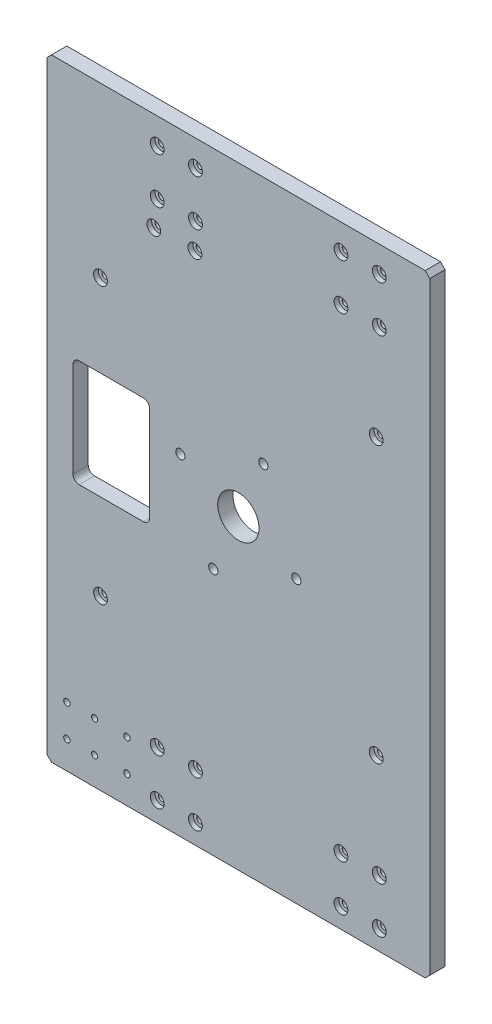
SolidWorks part; units mm, degrees
ref_plane "Plan de face" through (0, 0, 0) normal (0, 0, 1) x (1, 0, 0)
ref_plane "Plan de dessus" through (0, 0, 0) normal (0, 1, 0) x (1, 0, 0)
ref_plane "Plan de droite" through (0, 0, 0) normal (1, 0, 0) x (0, 0, -1)
sketch "Esquisse1" plane through (0, 0, 0) normal (0, 0, 1) x (1, 0, 0)
  line L1 (-125, -200) -> (125, -200)
  line L2 (-125, -200) -> (-125, 200)
  line L3 (-125, 200) -> (125, 200)
  line L4 (125, -200) -> (125, 200)
  line L5 (-125, -200) -> (125, 200) construction
  line L6 (-125, 200) -> (125, -200) construction
  point P0 (0, 0)
  dimension "D1" = 400
  dimension "D2" = 250
extrude "Boss.-Extru.1" add sketch "Esquisse1" along normal blind 10
ref_plane "Plan1" through (0, 0, 0) normal (1, 0, 0) x (0, 0, -1)
ref_plane "Plan2" through (0, 0, 0) normal (0, 1, 0) x (1, 0, 0)
sketch "Esquisse2" plane through (0, 0, 0) normal (0, 0, -1) x (-1, 0, 0)
  circle A0 centre (0, 0) radius 13.5
  dimension "D1" = 27
extrude "Enlèv. mat.-Extru.1" cut sketch "Esquisse2" against normal through all
chamfer "Chanfrein1" distance 3 angle 45 4 edges at (-125, -200, 5) (125, -200, 5) (125, 200, 5) (-125, 200, 5)
hole_wizard "Trou taraudé M51" positions "Esquisse6" profile "Esquisse5" tap size "M5" standard "ISO" end condition through all
sketch "Esquisse6" plane through (0, 0, 10) normal (0, 0, 1) x (1, 0, 0)
  point P0 (-72.6985, -161.0797)
  point P3 (-72.6985, -181.8387)
  point P6 (-111.9372, -181.8387)
  point P9 (-111.9372, -161.0797)
sketch "Esquisse5" plane through (-72.6985, -161.0797, 10) normal (1, 0, 0) x (0, -1, 0)
  line L0 (0, 0) -> (0, 10)
  line L1 (0, 10) -> (2.1, 10)
  line L2 (2.1, 10) -> (2.1, 0)
  line L5 (2.1, 0) -> (0, 0)
  line L11 (0, -6.35) -> (0, 107.95) construction
  dimension "Diamètre du trou pour taraudage jusqu'au prochain" = 4.2
  dimension "Profondeur du trou pour taraudage jusqu'au prochain" = 10
cosmetic thread "Filetage de perçage3" parameters "D2"=5
cosmetic thread "Filetage de perçage4" parameters "D2"=5
cosmetic thread "Filetage de perçage5" parameters "D2"=5
cosmetic thread "Filetage de perçage6" parameters "D2"=5
hole_wizard "Trous de centrage Ø4.0mm2" positions "Esquisse9" profile "Esquisse8" hole size "Ø4.0" standard "ISO" end condition through all
sketch "Esquisse9" plane through (0, 0, 10) normal (0, 0, 1) x (1, 0, 0)
  point P0 (-93.8631, -161.0797)
  point P3 (-93.8631, -181.8387)
sketch "Esquisse8" plane through (-93.8631, -161.0797, 10) normal (1, 0, 0) x (0, -1, 0)
  line L0 (0, 0) -> (0, 10)
  line L1 (0, 10) -> (2, 10)
  line L2 (2, 10) -> (2, 0)
  line L5 (2, 0) -> (0, 0)
  line L11 (0, -6.35) -> (0, 107.95) construction
  dimension "Diamètre du perçage jusqu'au prochain" = 4
  dimension "Profondeur du perçage jusqu'au prochain" = 10
sketch "Esquisse10" plane through (0, 0, 10) normal (0, 0, 1) x (1, 0, 0)
  circle A0 centre (0, 0) radius 41.25 construction
  dimension "D1" = 82.5
hole_wizard "Trous de centrage Ø6.0mm2" positions "Esquisse26" profile "Esquisse25" hole size "Ø6.0" standard "ISO" end condition through all
sketch "Esquisse26" plane through (0, 0, 10) normal (0, 0, 1) x (1, 0, 0)
  point P0 (16.3571, 37.8683)
  point P2 (37.8683, -16.3571)
  point P4 (-16.3571, -37.8683)
  point P6 (-37.8683, 16.3571)
sketch "Esquisse25" plane through (16.3571, 37.8683, 10) normal (1, 0, 0) x (0, -1, 0)
  line L0 (0, 0) -> (0, 10)
  line L1 (0, 10) -> (3, 10)
  line L2 (3, 10) -> (3, 0)
  line L5 (3, 0) -> (0, 0)
  line L11 (0, -6.35) -> (0, 107.95) construction
  dimension "Diamètre du perçage jusqu'au prochain" = 6
  dimension "Profondeur du perçage jusqu'au prochain" = 10
hole_wizard "Dégagement M41" positions "Esquisse28" profile "Esquisse27" hole size "M4" standard "JIS" end condition through all
sketch "Esquisse28" plane through (0, 0, 0) normal (0, 0, -1) x (-1, 0, 0)
  point P0 (28, -187)
  point P2 (28, -157)
  point P4 (53, -157)
  point P6 (53, -187)
sketch "Esquisse27" plane through (-28, -187, 0) normal (1, 0, 0) x (0, 1, 0)
  line L0 (0, 0) -> (0, 10)
  line L1 (0, 10) -> (2.25, 10)
  line L2 (2.25, 10) -> (2.25, 0)
  line L5 (2.25, 0) -> (0, 0)
  line L11 (0, -6.35) -> (0, 107.95) construction
  dimension "Diamètre du perçage jusqu'au prochain" = 4.5
  dimension "Profondeur du perçage jusqu'au prochain" = 10
pattern_linear "Répétition linéaire1" count 2 spacing 120 along (1, 0, 0) count 2 spacing 340 along (0, 1, 0) of "Dégagement M41"
hole_wizard "Chambrage pour vis à tête ronde bombée M41" positions "Esquisse30" profile "Esquisse29" counterbore size "M4" standard "Ansi Metric" end condition through all
sketch "Esquisse30" plane through (0, 0, 10) normal (0, 0, 1) x (1, 0, 0)
  point P0 (92, -157)
sketch "Esquisse29" plane through (92, -157, 10) normal (1, 0, 0) x (0, -1, 0)
  line L0 (0, 0) -> (0, 10)
  line L1 (0, 10) -> (2.25, 10)
  line L2 (2.25, 3.125) -> (2.25, 10)
  line L3 (2.25, 3.125) -> (2.275, 3.1)
  line L4 (2.275, 3.1) -> (4.5, 3.1)
  line L5 (4.5, 3.1) -> (4.5, 0)
  line L7 (0, 0) -> (4.5, 0)
  line L9 (-2.25, 3.125) -> (-2.275, 3.1) construction
  line L11 (0, -6.35) -> (0, 107.95) construction
  dimension "Diamètre du perçage jusqu'au prochain" = 4.5
  dimension "Profondeur du perçage jusqu'au prochain" = 10
  dimension "Diamètre du chambrage" = 9
  dimension "Profondeur du chambrage" = 3.1
  dimension "Diamètre du fraisage milieu" = 4.55
  dimension "Angle du fraisage milieu" = 90
pattern_linear "Répétition linéaire2" count 2 spacing 30 along (0, -1, 0) count 2 spacing 25 along (-1, 0, 0) of "Chambrage pour vis à tête ronde bombée M41"
pattern_linear "Répétition linéaire3" count 2 spacing 120 along (-1, 0, 0) count 2 spacing 340 along (0, 1, 0) of "Répétition linéaire2", "Chambrage pour vis à tête ronde bombée M41"
hole_wizard "Dégagement M42" positions "Esquisse32" profile "Esquisse31" hole size "M4" standard "JIS" end condition through all
sketch "Esquisse32" plane through (0, 0, 0) normal (0, 0, -1) x (-1, 0, 0)
  point P0 (90, -90)
  point P2 (90, 90)
  point P4 (-90, 90)
  point P6 (-90, -90)
sketch "Esquisse31" plane through (-90, -90, 0) normal (1, 0, 0) x (0, 1, 0)
  line L0 (0, 0) -> (0, 10)
  line L1 (0, 10) -> (2.25, 10)
  line L2 (2.25, 10) -> (2.25, 0)
  line L5 (2.25, 0) -> (0, 0)
  line L11 (0, -6.35) -> (0, 107.95) construction
  dimension "Diamètre du perçage jusqu'au prochain" = 4.5
  dimension "Profondeur du perçage jusqu'au prochain" = 10
hole_wizard "Chambrage pour vis à tête ronde bombée M42" positions "Esquisse34" profile "Esquisse33" counterbore size "M4" standard "Ansi Metric" end condition through all
sketch "Esquisse34" plane through (0, 0, 10) normal (0, 0, 1) x (1, 0, 0)
  point P0 (-90, -90)
  point P2 (-90, 90)
  point P4 (90, -90)
  point P6 (90, 90)
sketch "Esquisse33" plane through (-90, -90, 10) normal (1, 0, 0) x (0, -1, 0)
  line L0 (0, 0) -> (0, 10)
  line L1 (0, 10) -> (2.25, 10)
  line L2 (2.25, 3.125) -> (2.25, 10)
  line L3 (2.25, 3.125) -> (2.275, 3.1)
  line L4 (2.275, 3.1) -> (4.5, 3.1)
  line L5 (4.5, 3.1) -> (4.5, 0)
  line L7 (0, 0) -> (4.5, 0)
  line L9 (-2.25, 3.125) -> (-2.275, 3.1) construction
  line L11 (0, -6.35) -> (0, 107.95) construction
  dimension "Diamètre du perçage jusqu'au prochain" = 4.5
  dimension "Profondeur du perçage jusqu'au prochain" = 10
  dimension "Diamètre du chambrage" = 9
  dimension "Profondeur du chambrage" = 3.1
  dimension "Diamètre du fraisage milieu" = 4.55
  dimension "Angle du fraisage milieu" = 90
hole_wizard "Dégagement M43" positions "Esquisse36" profile "Esquisse35" hole size "M4" standard "JIS" end condition through all
sketch "Esquisse36" plane through (0, 0, 0) normal (0, 0, -1) x (-1, 0, 0)
  point P0 (55.199, 135.7065)
  point P2 (28.3418, 135.9918)
sketch "Esquisse35" plane through (-55.199, 135.7065, 0) normal (1, 0, 0) x (0, 1, 0)
  line L0 (0, 0) -> (0, 10)
  line L1 (0, 10) -> (2.25, 10)
  line L2 (2.25, 10) -> (2.25, 0)
  line L5 (2.25, 0) -> (0, 0)
  line L11 (0, -6.35) -> (0, 107.95) construction
  dimension "Diamètre du perçage jusqu'au prochain" = 4.5
  dimension "Profondeur du perçage jusqu'au prochain" = 10
hole_wizard "Chambrage pour vis à tête ronde bombée M43" positions "Esquisse38" profile "Esquisse37" counterbore size "M4" standard "Ansi Metric" end condition through all
sketch "Esquisse38" plane through (0, 0, 10) normal (0, 0, 1) x (1, 0, 0)
  point P0 (-55.199, 135.7065)
  point P2 (-28.3418, 135.9918)
sketch "Esquisse37" plane through (-55.199, 135.7065, 10) normal (1, 0, 0) x (0, -1, 0)
  line L0 (0, 0) -> (0, 10)
  line L1 (0, 10) -> (2.25, 10)
  line L2 (2.25, 3.125) -> (2.25, 10)
  line L3 (2.25, 3.125) -> (2.275, 3.1)
  line L4 (2.275, 3.1) -> (4.5, 3.1)
  line L5 (4.5, 3.1) -> (4.5, 0)
  line L7 (0, 0) -> (4.5, 0)
  line L9 (-2.25, 3.125) -> (-2.275, 3.1) construction
  line L11 (0, -6.35) -> (0, 107.95) construction
  dimension "Diamètre du perçage jusqu'au prochain" = 4.5
  dimension "Profondeur du perçage jusqu'au prochain" = 10
  dimension "Diamètre du chambrage" = 9
  dimension "Profondeur du chambrage" = 3.1
  dimension "Diamètre du fraisage milieu" = 4.55
  dimension "Angle du fraisage milieu" = 90
sketch "Sketch2" plane through (0, 0, 10) normal (0, 0, 1) x (1, 0, 0)
  line L0 (122, 200) -> (-122, 200) construction
  line L1 (-104, 36) -> (-62, 36)
  line L2 (-108, 32) -> (-108, -30)
  line L3 (-104, -34) -> (-62, -34)
  line L4 (-58, 32) -> (-58, -30)
  line L5 (-108, 36) -> (-58, -34) construction
  line L6 (-108, -34) -> (-58, 36) construction
  line L8 (-125, 197) -> (-125, -197) construction
  arc A0 (-62, 36) -> (-58, 32) centre (-62, 32) cw
  arc A1 (-104, 36) -> (-108, 32) centre (-104, 32) ccw
  arc A2 (-108, -30) -> (-104, -34) centre (-104, -30) ccw
  arc A3 (-58, -30) -> (-62, -34) centre (-62, -30) cw
  point P0 (-83, 1)
  dimension "D5" = 4
  dimension "D1" = 70
  dimension "D2" = 50
  dimension "D3" = 164
  dimension "D4" = 17
extrude "Cut-Extrude1" cut sketch "Sketch2" against normal blind 10
